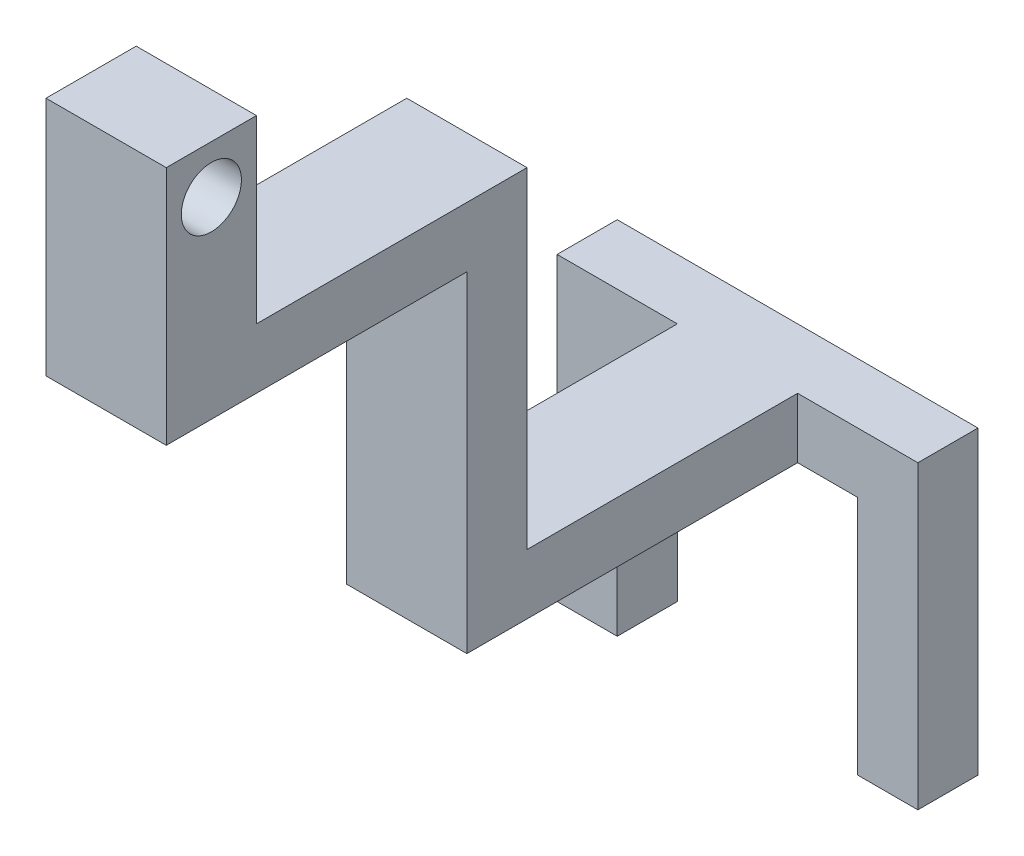
SolidWorks part; units mm, degrees
ref_plane "Přední rovina" through (0, 0, 0) normal (0, 0, 1) x (1, 0, 0)
ref_plane "Horní rovina" through (0, 0, 0) normal (0, 1, 0) x (1, 0, 0)
ref_plane "Pravá rovina" through (0, 0, 0) normal (1, 0, 0) x (0, 0, -1)
sketch "Skica1" plane through (0, 0, 0) normal (0, 0, 1) x (1, 0, 0)
  line L0 (0, 0) -> (60, 0)
  line L1 (60, 0) -> (60, -50)
  line L2 (60, -50) -> (50, -50)
  line L3 (50, -50) -> (50, -10)
  line L4 (50, -10) -> (10, -10)
  line L5 (10, -10) -> (10, -50)
  line L6 (10, -50) -> (0, -50)
  line L7 (0, -50) -> (0, 0)
  dimension "D1" = 60
  dimension "D2" = 40
  dimension "D3" = 10
  dimension "D4" = 10
  dimension "D5" = 40
  dimension "D6" = 40
  dimension "D7" = 10
extrude "Přidat vysunutím1" add sketch "Skica1" along normal blind 10
sketch "Skica2" plane through (0, 0, 10) normal (0, 0, 1) x (1, 0, 0)
  line L0 (60, 0) -> (0, 0) construction
  line L1 (20, 0) -> (40, 0)
  line L2 (20, 0) -> (20, -10)
  line L3 (20, -10) -> (40, -10)
  line L4 (40, 0) -> (40, -10)
  line L5 (10, -10) -> (50, -10) construction
  line L6 (0, 0) -> (0, -50) construction
  dimension "D1" = 20
  dimension "D2" = 20
extrude "Přidat vysunutím2" add sketch "Skica2" along normal blind 55
sketch "Skica4" plane through (0, 0, 0) normal (0, 1, 0) x (1, 0, 0)
  line L0 (40, -65) -> (40, -10) construction
  line L1 (20, -65) -> (40, -65)
  line L2 (20, -65) -> (20, -55)
  line L3 (20, -55) -> (40, -55)
  line L4 (40, -65) -> (40, -55)
  dimension "D1" = 10
extrude "Přidat vysunutím3" add sketch "Skica4" along normal blind 55
sketch "Skica5" plane through (0, 0, 65) normal (0, 0, 1) x (1, 0, 0)
  line L0 (40, -10) -> (40, 55) construction
  line L1 (20, 55) -> (40, 55)
  line L2 (20, 55) -> (20, 45)
  line L3 (20, 45) -> (40, 45)
  line L4 (40, 55) -> (40, 45)
  dimension "D1" = 10
extrude "Přidat vysunutím4" add sketch "Skica5" along normal blind 50
sketch "Skica6" plane through (0, 55, 0) normal (0, 1, 0) x (1, 0, 0)
  line L0 (40, -115) -> (40, -55) construction
  line L1 (20, -115) -> (40, -115)
  line L2 (20, -115) -> (20, -100)
  line L3 (20, -100) -> (40, -100)
  line L4 (40, -115) -> (40, -100)
  dimension "D1" = 15
extrude "Přidat vysunutím5" add sketch "Skica6" along normal blind 30
sketch "Skica7" plane through (40, 0, 0) normal (1, 0, 0) x (0, 0, -1)
  line L0 (-100, 85) -> (-100, 55) construction
  line L1 (-115, 85) -> (-100, 85) construction
  circle A0 centre (-107.5, 77) radius 5
  dimension "D1" = 10
  dimension "D2" = 7.5
  dimension "D3" = 8
extrude "Odebrat vysunutím1" cut sketch "Skica7" against normal blind 20
